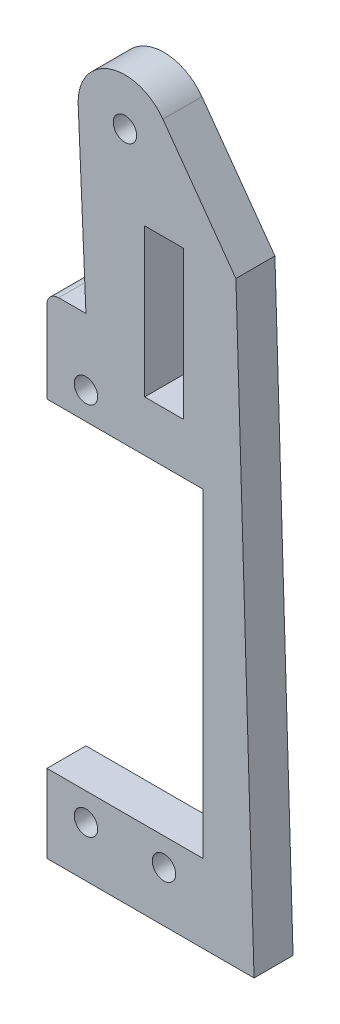
SolidWorks part; units mm, degrees
ref_plane "Plan de face" through (0, 0, 0) normal (0, 0, 1) x (1, 0, 0)
ref_plane "Plan de dessus" through (0, 0, 0) normal (0, 1, 0) x (1, 0, 0)
ref_plane "Plan de droite" through (0, 0, 0) normal (1, 0, 0) x (0, 0, -1)
sketch "Esquisse1" plane through (0, 0, 0) normal (0, 0, 1) x (1, 0, 0)
  line L0 (0, 10) -> (0, 0)
  line L1 (0, 0) -> (26.5541, 0)
  line L2 (10, 10) -> (10, 51) construction
  line L3 (0, 63) -> (5, 63)
  line L4 (12.5289, 76.5) -> (12.5289, 57.5)
  line L5 (11, 51) -> (0, 51)
  line L6 (12.5289, 76.5) -> (17.5289, 76.5)
  line L7 (20, 10) -> (11, 10)
  line L8 (0, 30.5) -> (0, 10)
  line L9 (0, 30.5) -> (20, 30.5) construction
  line L10 (20, 10) -> (20, 51)
  line L11 (20, 51) -> (11, 51)
  line L12 (14.8704, 89.5041) -> (24.2264, 76.5)
  line L13 (24.2264, 76.5) -> (26.5541, 0)
  line L14 (12.5289, 57.5) -> (17.5289, 57.5)
  line L15 (17.5289, 57.5) -> (17.5289, 76.5)
  line L16 (4.0057, 85.7379) -> (5, 63)
  line L18 (11, 10) -> (0, 10)
  line L25 (0, 63) -> (0, 51)
  line L26 (17.5289, 76.5) -> (24.2264, 76.5) construction
  circle A0 centre (5, 54.5) radius 1.5
  circle A1 centre (15, 54.5) radius 1.5 construction
  circle A2 centre (15, 6.5) radius 1.5
  circle A3 centre (5, 6.5) radius 1.5
  circle A4 centre (10, 86) radius 1.5
  arc A6 (4.0057, 85.7379) -> (14.8704, 89.5041) centre (10, 86) cw
  circle A7 centre (10, 86) radius 1.5 construction
  dimension "D6" = 20
  dimension "D8" = 5
  dimension "D11" = 3
  dimension "D16" = 10
  dimension "D5" = 3
  dimension "D13" = 6
  dimension "D1" = 41
  dimension "D2" = 12
  dimension "D3" = 3.5
  dimension "D4" = 5
  dimension "D7" = 5
  dimension "D9" = 5
  dimension "D10" = 91.743
extrude "Boss.-Extru.1" add sketch "Esquisse1" along normal blind 5
fillet "Congé3" radius 1.5 1 edges at (0, 63, 2.5)
